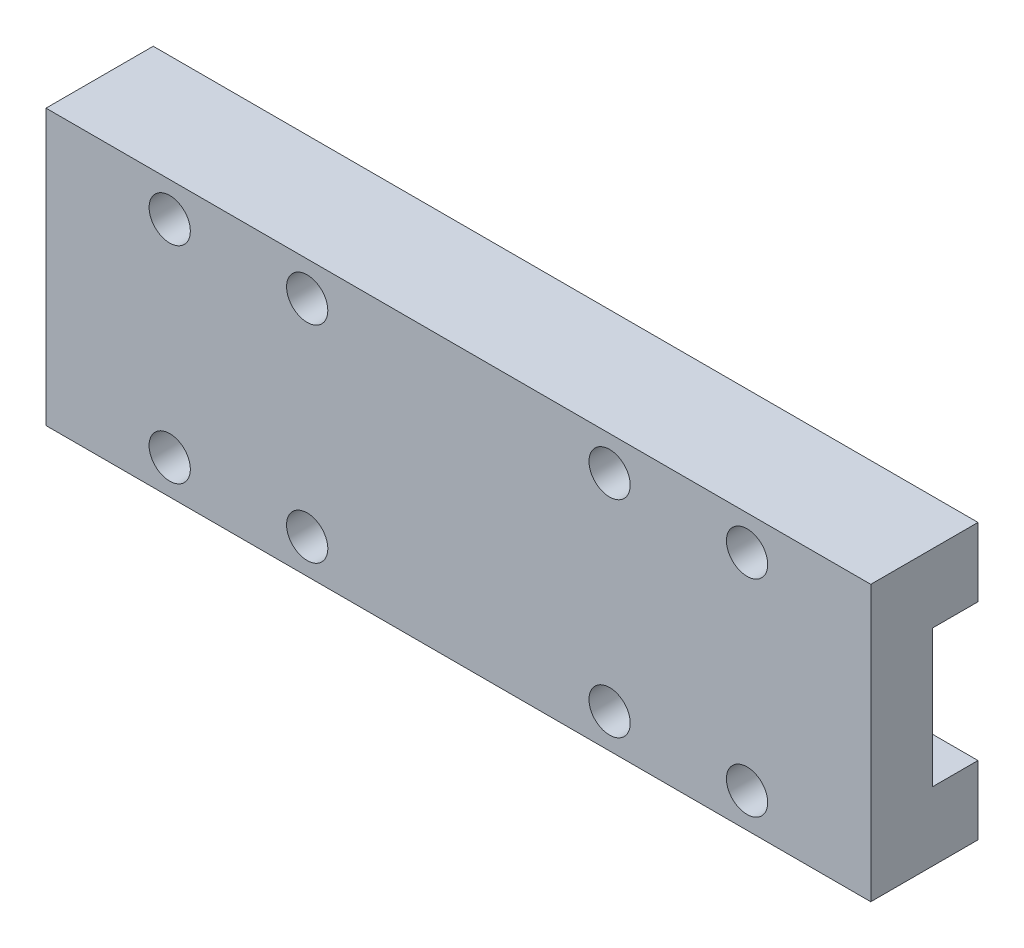
SolidWorks part; units mm, degrees
ref_plane "Plan de face" through (0, 0, 0) normal (0, 0, 1) x (1, 0, 0)
ref_plane "Plan de dessus" through (0, 0, 0) normal (0, 1, 0) x (1, 0, 0)
ref_plane "Plan de droite" through (0, 0, 0) normal (1, 0, 0) x (0, 0, -1)
sketch "Esquisse1" plane through (0, 0, 0) normal (0, 0, 1) x (1, 0, 0)
  line L1 (0, 0) -> (-60, 0)
  line L2 (0, 0) -> (0, 20)
  line L3 (0, 20) -> (-60, 20)
  line L4 (-60, 0) -> (-60, 20)
  dimension "D1" = 60
  dimension "D2" = 20
extrude "Boss.-Extru.1" add sketch "Esquisse1" along normal blind 7.8
sketch "Esquisse2" plane through (0, 0, 0) normal (0, 0, -1) x (-1, 0, 0)
  line L0 (0, 0) -> (0, 20) construction
  line L1 (0, 15) -> (60, 15)
  line L2 (0, 15) -> (0, 5)
  line L3 (0, 5) -> (60, 5)
  line L4 (60, 15) -> (60, 5)
  line L5 (60, 20) -> (60, 0) construction
  line L6 (60, 0) -> (0, 0) construction
  dimension "D1" = 10
  dimension "D2" = 5
extrude "Enlèv. mat.-Extru.1" cut sketch "Esquisse2" against normal blind 3.3
sketch "Esquisse4" plane through (0, 0, 7.8) normal (0, 0, 1) x (1, 0, 0)
  line L0 (-30, 20) -> (-30, 0) construction
  line L1 (0, 20) -> (-60, 20) construction
  line L2 (-60, 0) -> (0, 0) construction
  line L3 (-60, 10) -> (0, 10) construction
  line L4 (-60, 20) -> (-60, 0) construction
  line L5 (0, 0) -> (0, 20) construction
  circle A0 centre (-51, 17.5) radius 1.5
  circle A1 centre (-41, 17.5) radius 1.5
  circle A2 centre (-19, 17.5) radius 1.5
  circle A3 centre (-9, 17.5) radius 1.5
  circle A4 centre (-9, 2.5) radius 1.5
  circle A5 centre (-19, 2.5) radius 1.5
  circle A6 centre (-41, 2.5) radius 1.5
  circle A7 centre (-51, 2.5) radius 1.5
  dimension "D1" = 10
  dimension "D2" = 10
  dimension "D3" = 9
  dimension "D4" = 9
  dimension "D5" = 3
  dimension "D6" = 3
  dimension "D7" = 3
  dimension "D8" = 3
  dimension "D9" = 22
  dimension "D10" = 2.5
  dimension "D11" = 2.5
  dimension "D12" = 2.5
extrude "Enlèv. mat.-Extru.2" cut sketch "Esquisse4" against normal blind 3
